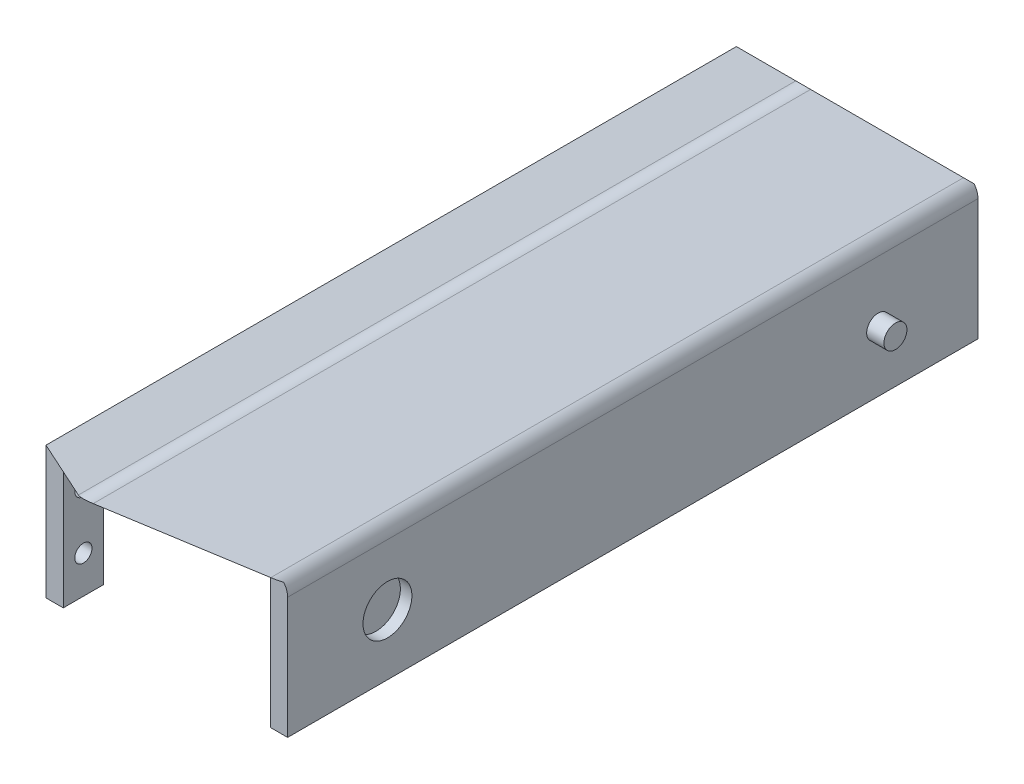
SolidWorks part; units mm, degrees
ref_plane "Front Plane" through (0, 0, 0) normal (0, 0, 1) x (1, 0, 0)
ref_plane "Top Plane" through (0, 0, 0) normal (0, 1, 0) x (1, 0, 0)
ref_plane "Right Plane" through (0, 0, 0) normal (1, 0, 0) x (0, 0, -1)
sketch "Sketch2" plane through (0, 0, 0) normal (0, 0, 1) x (1, 0, 0)
  line L0 (-18, 0) -> (-21, 0)
  line L5 (-21, 0) -> (-21, 23)
  line L8 (21, 23) -> (21, 0)
  line L11 (21, 0) -> (18, 0)
  line L16 (-21, 0) -> (-18, 0)
  line L21 (-18, 0) -> (-18, 20)
  line L23 (18, 20) -> (18, 0)
  line L25 (0, 33) -> (21, 23)
  line L26 (0, 33) -> (-21, 23)
  line L27 (-18, 20) -> (-18, 23)
  line L28 (18, 20) -> (18, 23)
  line L29 (-18, 23) -> (0, 31.5565)
  line L30 (0, 31.5565) -> (18, 23)
extrude "Boss-Extrude1" add sketch "Sketch2" along normal blind 120 contours L29 L30 L28 L23 L11 L8 L25 L26 L5 L0 L21 L27
sketch "Sketch3" plane through (0, 0, 120) normal (0, 0, 1) x (1, 0, 0)
  line L0 (-18, 23) -> (-21, 23)
  line L1 (-21, 23) -> (0, 33)
  line L2 (0, 33) -> (21, 23)
  line L3 (21, 23) -> (18, 23)
  line L4 (18, 23) -> (0, 31.5565)
  line L5 (0, 31.5565) -> (-18, 23)
extrude "Boss-Extrude2" add sketch "Sketch3" along normal blind 15
sketch "Sketch4" plane through (-21, 0, 0) normal (-1, 0, 0) x (0, 0, 1)
  line L0 (135, 23) -> (120, 23)
  line L1 (120, 23) -> (135, 33)
  line L2 (135, 33) -> (135, 23)
extrude "Cut-Extrude1" cut sketch "Sketch4" against normal blind 43
sketch "Sketch5" plane through (21, 0, 0) normal (1, 0, 0) x (0, 0, -1)
  line L0 (0, 23) -> (0, 33)
  line L1 (0, 33) -> (-10, 33)
  line L2 (-135, 33) -> (0, 33) construction
  line L3 (-10, 33) -> (0, 23)
extrude "Cut-Extrude2" cut sketch "Sketch5" against normal blind 43
fillet "Fillet1" radius 3 1 edges at (0, 33, 72.5)
fillet "Fillet2" radius 3 1 edges at (21, 23, 60)
sketch "Sketch6" plane through (-21, 0, 0) normal (-1, 0, 0) x (0, 0, 1)
  line L0 (0, 0) -> (0, 23)
  line L1 (0, 23) -> (7, 23)
  line L2 (120, 23) -> (0, 23) construction
  line L3 (7, 23) -> (7, 0)
  line L4 (120, 0) -> (0, 0) construction
  line L5 (7, 0) -> (0, 0)
  line L6 (7, 23) -> (46.5, 23)
  line L7 (46.5, 23) -> (46.5, 0)
  line L8 (46.5, 0) -> (53.5, 0)
  line L9 (53.5, 0) -> (53.5, 23)
  line L10 (53.5, 23) -> (46.5, 23)
  line L11 (7, 0) -> (46.5, 0)
  line L12 (60, 23) -> (60, 0) construction
  line L13 (26.75, 0) -> (26.75, 23) construction
  line L14 (73.5, 0) -> (66.5, 0)
  line L15 (66.5, 23) -> (73.5, 23)
  line L16 (66.5, 0) -> (66.5, 23)
  line L17 (73.5, 23) -> (73.5, 0)
  line L18 (113, 23) -> (73.5, 23)
  line L19 (113, 0) -> (73.5, 0)
  line L20 (113, 0) -> (120, 0)
  line L21 (120, 0) -> (120, 23)
  line L22 (120, 23) -> (113, 23)
  line L23 (113, 23) -> (113, 0)
  circle A0 centre (3.5, 16.5) radius 1.5
  circle A1 centre (3.5, 6.5) radius 1.5
  circle A2 centre (50, 6.5) radius 1.5
  circle A3 centre (50, 16.5) radius 1.5
  circle A4 centre (70, 6.5) radius 1.5
  circle A5 centre (70, 16.5) radius 1.5
  circle A6 centre (116.5, 6.5) radius 1.5
  circle A7 centre (116.5, 16.5) radius 1.5
  line M8 (0, 0) -> (120, 0)
  line M10 (120, 23) -> (0, 23)
extrude "Cut-Extrude3" cut sketch "Sketch6" against normal blind 3 contours L7 L3 M10 M8 | L23 L17 M10 M8 | A6 | A7 | A4 | A3 | A0 | A1 | A2 | A5
sketch "Sketch7" plane through (21, 0, 0) normal (1, 0, 0) x (0, 0, -1)
  line L0 (-120, 21.1058) -> (-120, 0) construction
  circle A0 centre (-102.6492, 10.5529) radius 4.25
  point P4 (-120, 10.5529)
  dimension "D1" = 17.3508
extrude "Cut-Extrude4" cut sketch "Sketch7" against normal blind 2
sketch "Sketch8" plane through (21, 0, 0) normal (1, 0, 0) x (0, 0, -1)
  line L0 (0, 21.1058) -> (0, 0) construction
  circle A0 centre (-17.3508, 10.5529) radius 4.25
  point P4 (0, 10.5529)
  dimension "D1" = 17.3508
extrude "Cut-Extrude5" cut sketch "Sketch8" against normal blind 2
sketch "Sketch9" plane through (19, 0, 0) normal (1, 0, 0) x (0, 0, -1)
  circle A0 centre (-17.3508, 10.5529) radius 4.25
extrude "Boss-Extrude3" add sketch "Sketch9" along normal blind 2
sketch "Sketch10" plane through (21, 0, 0) normal (1, 0, 0) x (0, 0, -1)
  circle A0 centre (-17.3508, 10.5529) radius 2
extrude "Boss-Extrude4" add sketch "Sketch10" along normal blind 3
